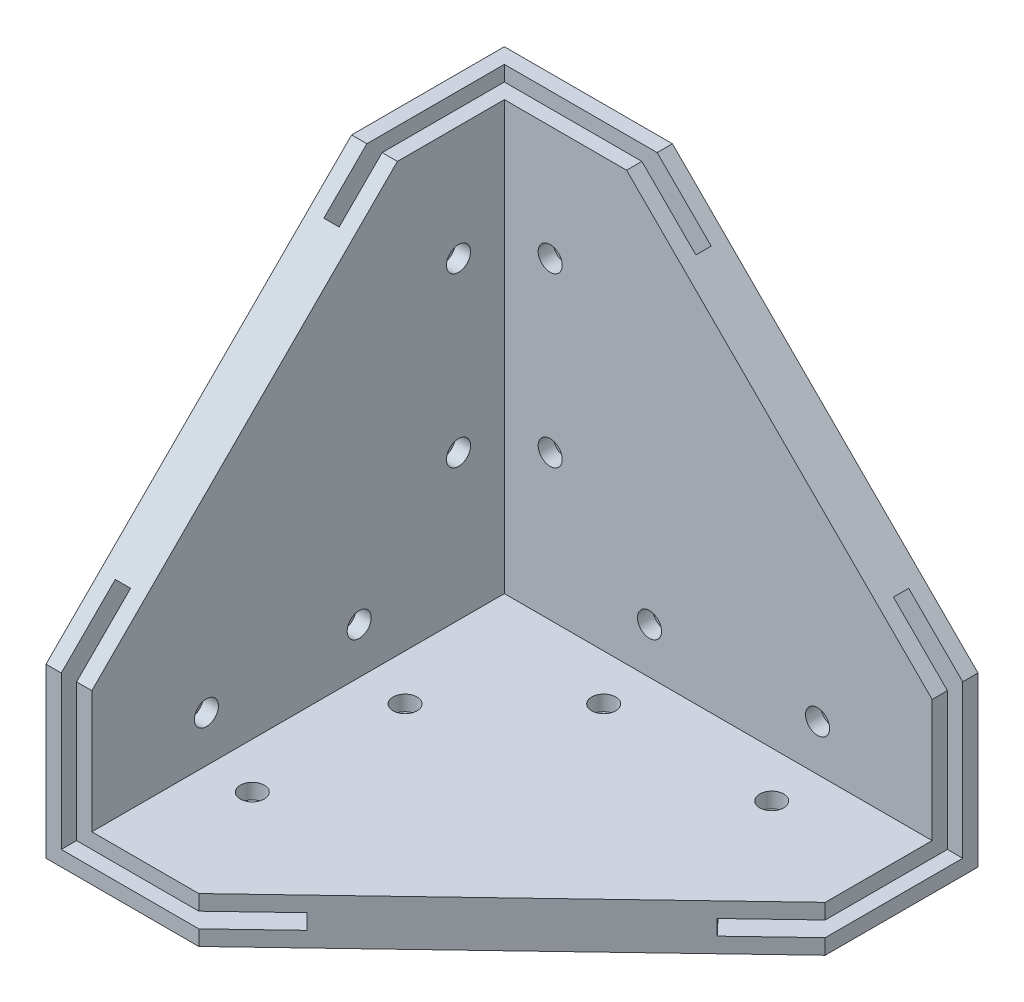
SolidWorks part; units mm, degrees
ref_plane "Front Plane" through (0, 0, 0) normal (0, 0, 1) x (1, 0, 0)
ref_plane "Top Plane" through (0, 0, 0) normal (0, 1, 0) x (1, 0, 0)
ref_plane "Right Plane" through (0, 0, 0) normal (1, 0, 0) x (0, 0, -1)
sketch "Sketch1" plane through (0, 0, 0) normal (0, 0, 1) x (1, 0, 0)
  line L0 (0, 76.2) -> (0, 0)
  line L1 (0, 0) -> (76.2, 0)
  line L2 (76.2, 0) -> (76.2, 25.4)
  line L3 (76.2, 25.4) -> (25.4, 76.2)
  line L4 (25.4, 76.2) -> (0, 76.2)
  dimension "D1" = 76.2
  dimension "D2" = 76.2
  dimension "D3" = 25.4
  dimension "D4" = 25.4
extrude "Boss-Extrude1" add sketch "Sketch1" along normal blind 2.54
sketch "Sketch3" plane through (0, 0, 0) normal (-1, 0, 0) x (0, 0, 1)
  line L0 (0, 76.2) -> (25.4, 76.2)
  line L2 (0, 76.2) -> (0, 0)
  line L3 (0, 0) -> (76.2, 0)
  line L4 (76.2, 0) -> (76.2, 25.4)
  line L6 (25.4, 76.2) -> (76.2, 25.4)
  dimension "D1" = 25.4
  dimension "D2" = 25.4
  dimension "D3" = 76.2
extrude "Boss-Extrude2" add sketch "Sketch3" along normal blind 2.54
sketch "Sketch5" plane through (0, 0, 0) normal (0, -1, 0) x (1, 0, 0)
  line L0 (-2.54, 76.2) -> (-2.54, 0)
  line L1 (-2.54, 0) -> (-2.54, 76.2) construction
  line L2 (-2.54, 0) -> (76.2, 0)
  line L3 (76.2, 0) -> (76.2, 25.4)
  line L4 (76.2, 25.4) -> (22.86, 76.2)
  line L5 (22.86, 76.2) -> (-2.54, 76.2)
  line L6 (-2.54, 76.2) -> (0, 76.2) construction
  dimension "D1" = 25.4
  dimension "D2" = 25.4
extrude "Boss-Extrude3" add sketch "Sketch5" along normal blind 2.54
sketch "Sketch6" plane through (0, 0, 0) normal (0, 0, 1) x (1, 0, 0)
  line L0 (22.86, 0) -> (0, 0) construction
  line L1 (2.54, 0) -> (5.08, 0)
  line L2 (2.54, 0) -> (2.54, 76.2)
  line L3 (2.54, 76.2) -> (5.08, 76.2)
  line L4 (5.08, 0) -> (5.08, 76.2)
  line L5 (25.4, 76.2) -> (0, 76.2) construction
  line L6 (0, 76.2) -> (0, 0) construction
  dimension "D1" = 2.54
  dimension "D2" = 2.54
extrude "Boss-Extrude4" add sketch "Sketch6" along direction (0, 0, -1) on the side of the normal blind 76.2
sketch "Sketch7" plane through (0, 0, 0) normal (1, 0, 0) x (0, 0, -1)
  line L0 (-25.4, 76.2) -> (-76.2, 25.4)
  line L1 (-76.2, 25.4) -> (-76.2, 76.2)
  line L2 (-76.2, 76.2) -> (-25.4, 76.2)
extrude "Cut-Extrude1" cut sketch "Sketch7" along normal up to next
sketch "Sketch8" plane through (0, 0, 0) normal (1, 0, 0) x (0, 0, -1)
  line L0 (-25.4, 76.2) -> (-2.54, 76.2) construction
  line L1 (-7.62, 76.2) -> (-5.08, 76.2)
  line L2 (-7.62, 76.2) -> (-7.62, -2.54)
  line L3 (-7.62, -2.54) -> (-5.08, -2.54)
  line L4 (-5.08, 76.2) -> (-5.08, -2.54)
  line L5 (0, -2.54) -> (-25.4, -2.54) construction
  line L6 (-2.54, 76.2) -> (-2.54, 0) construction
  dimension "D1" = 2.54
  dimension "D2" = 2.54
extrude "Boss-Extrude5" add sketch "Sketch8" along normal blind 76.2
sketch "Sketch9" plane through (0, 0, 0) normal (0, 0, 1) x (1, 0, 0)
  line L0 (76.2, 25.4) -> (25.4, 76.2)
  line L1 (25.4, 76.2) -> (76.2, 76.2)
  line L2 (76.2, 76.2) -> (76.2, 25.4)
extrude "Cut-Extrude2" cut sketch "Sketch9" along normal up to next
sketch "Sketch10" plane through (0, 0, 0) normal (0, 0, 1) x (1, 0, 0)
  line L0 (-2.54, -2.54) -> (-2.54, 25.4) construction
  line L1 (-2.54, 2.54) -> (76.2, 2.54)
  line L2 (-2.54, 2.54) -> (-2.54, 5.08)
  line L3 (-2.54, 5.08) -> (76.2, 5.08)
  line L4 (76.2, 2.54) -> (76.2, 5.08)
  line L5 (76.2, 25.4) -> (76.2, 0) construction
  line L6 (5.08, 0) -> (76.2, 0) construction
  dimension "D1" = 2.54
  dimension "D2" = 2.54
extrude "Boss-Extrude6" add sketch "Sketch10" along normal blind 76.2
sketch "Sketch11" plane through (0, 0, 0) normal (0, 1, 0) x (1, 0, 0)
  line L0 (22.86, -76.2) -> (76.2, -25.4)
  line L1 (76.2, -25.4) -> (76.2, -76.2)
  line L2 (76.2, -76.2) -> (22.86, -76.2)
extrude "Cut-Extrude3" cut sketch "Sketch11" along normal up to next
sketch "Sketch12" plane through (0, 0, 0) normal (1, 0, 0) x (0, 0, -1)
  line L0 (-5.08, 5.08) -> (-5.08, 2.54)
  line L1 (-5.08, 2.54) -> (-7.62, 2.54)
  line L2 (-7.62, 2.54) -> (-7.62, 0)
  line L3 (-7.62, 2.54) -> (-7.62, 0) construction
  line L4 (-7.62, 0) -> (-2.54, 0)
  line L5 (-2.54, 0) -> (-2.54, 5.08)
  line L6 (-2.54, 5.08) -> (-5.08, 5.08)
extrude "Cut-Extrude5" cut sketch "Sketch12" along normal through all
sketch "Sketch13" plane through (0, 0, 0) normal (0, 1, 0) x (1, 0, 0)
  line L0 (0, -2.54) -> (0, -7.62)
  line L1 (0, -7.62) -> (2.54, -7.62)
  line L2 (2.54, -7.62) -> (2.54, -5.08)
  line L3 (2.54, -5.08) -> (2.54, -2.54) construction
  line L4 (2.54, -5.08) -> (5.08, -5.08)
  line L5 (5.08, -5.08) -> (5.08, -2.54)
  line L6 (5.08, -2.54) -> (0, -2.54)
extrude "Cut-Extrude6" cut sketch "Sketch13" along normal through all
sketch "Sketch15" plane through (0, 0, 2.54) normal (0, 0, 1) x (1, 0, 0)
  line L0 (2.54, 5.08) -> (0, 5.08)
  line L1 (0, 5.08) -> (0, 0)
  line L2 (0, 0) -> (5.08, 0)
  line L3 (0, 0) -> (76.2, 0) construction
  line L4 (22.86, 0) -> (5.08, 0) construction
  line L5 (5.08, 0) -> (5.08, 2.54)
  line L6 (5.08, 0) -> (5.08, 2.54) construction
  line L7 (5.08, 2.54) -> (2.54, 2.54)
  line L8 (2.54, 2.54) -> (2.54, 5.08)
extrude "Cut-Extrude9" cut sketch "Sketch15" along normal blind 76.2
sketch "Sketch17" plane through (0, 0, 0) normal (0, 0, -1) x (-1, 0, 0)
  line L0 (-67.2197, 34.3803) -> (-34.3803, 67.2197)
  line L1 (-76.2, 25.4) -> (-25.4, 76.2) construction
  line L2 (-34.3803, 67.2197) -> (-30.7882, 63.6276)
  line L3 (-30.7882, 63.6276) -> (-63.6276, 30.7882)
  line L4 (-63.6276, 30.7882) -> (-67.2197, 34.3803)
  dimension "D1" = 12.7
  dimension "D2" = 12.7
  dimension "D3" = 5.08
extrude "Boss-Extrude7" add sketch "Sketch17" against normal up to surface (7.62 mm away) up to face at (37.592, 37.592, 7.62)
sketch "Sketch18" plane through (0, 0, 0) normal (0, 1, 0) x (1, 0, 0)
  line L0 (32.0566, -67.4414) -> (67.0034, -34.1586)
  line L1 (76.2, -25.4) -> (22.86, -76.2) construction
  line L2 (67.0034, -34.1586) -> (63.5, -30.48)
  line L3 (63.5, -30.48) -> (28.5531, -63.7628)
  line L4 (28.5531, -63.7628) -> (32.0566, -67.4414)
  dimension "D1" = 12.7
  dimension "D2" = 12.7
  dimension "D3" = 5.08
extrude "Boss-Extrude8" add sketch "Sketch18" along normal up to surface (5.08 mm away) up to face at (37.084, 5.08, 38.608)
sketch "Sketch19" plane through (0, 0, 0) normal (1, 0, 0) x (0, 0, -1)
  line L0 (-32.545, 69.055) -> (-67.2197, 34.3803)
  line L1 (-76.2, 25.4) -> (-25.4, 76.2) construction
  line L2 (-67.2197, 34.3803) -> (-63.6276, 30.7882)
  line L3 (-63.6276, 30.7882) -> (-28.9529, 65.4629)
  line L4 (-28.9529, 65.4629) -> (-32.545, 69.055)
  point P4 (-49.8824, 51.7176)
  dimension "D1" = 10.1046
  dimension "D2" = 12.7
  dimension "D3" = 5.08
extrude "Boss-Extrude9" add sketch "Sketch19" along normal up to surface (5.08 mm away) up to face at (5.08, 37.592, 38.608)
sketch "Sketch34" plane through (0, 0, 0) normal (1, 0, 0) x (0, 0, -1)
  line L0 (-15.24, 89.2211) -> (-15.24, -21.4288) construction
  line L1 (12.0246, 12.7) -> (-100.539, 12.7) construction
  line L2 (0, 76.2) -> (0, -2.54) construction
  line L3 (-76.2, -2.54) -> (0, -2.54) construction
  line L4 (19.1577, 57.15) -> (-54.087, 57.15) construction
  line L5 (19.1577, 29.21) -> (-54.087, 29.21) construction
  line L6 (-57.15, 27.3793) -> (-57.15, -35.5499) construction
  line L7 (-31.75, 27.3793) -> (-31.75, -35.5499) construction
  line L8 (-76.2, -2.54) -> (-76.2, 25.4) construction
  circle A0 centre (-15.24, 57.15) radius 2
  circle A1 centre (-15.24, 29.21) radius 2
  circle A2 centre (-31.75, 12.7) radius 2
  circle A3 centre (-57.15, 12.7) radius 2
  point P27 (0, 0)
  point P28 (-57.15, 12.7)
  dimension "D7" = 4
  dimension "D8" = 4
  dimension "D9" = 4
  dimension "D10" = 4
  dimension "D1" = 15.24
  dimension "D2" = 15.24
  dimension "D3" = 19.05
  dimension "D4" = 31.75
  dimension "D5" = 31.75
  dimension "D6" = 19.05
extrude "Cut-Extrude11" cut sketch "Sketch34" against normal mid plane 25.4
sketch "Sketch35" plane through (0, 0, 0) normal (0, 1, 0) x (1, 0, 0)
  line L0 (12.7, -87.9891) -> (12.7, 14.1496) construction
  line L1 (-2.54, -76.2) -> (-2.54, 0) construction
  line L2 (-9.517, -15.24) -> (98.4386, -15.24) construction
  line L3 (-2.54, 0) -> (76.2, 0) construction
  line L4 (-9.517, -57.15) -> (98.4386, -57.15) construction
  line L5 (22.86, -76.2) -> (-2.54, -76.2) construction
  line L6 (-9.517, -31.75) -> (98.4386, -31.75) construction
  line L7 (57.15, 14.1496) -> (57.15, -87.9891) construction
  line L8 (57.15, -87.9891) -> (57.15, 14.1496) construction
  line L9 (29.21, -87.9891) -> (29.21, 14.1496) construction
  line L10 (76.2, 0) -> (76.2, -25.4) construction
  circle A0 centre (12.7, -57.15) radius 2
  circle A1 centre (12.7, -31.75) radius 2
  circle A2 centre (29.21, -15.24) radius 2
  circle A3 centre (57.15, -15.24) radius 2
  dimension "D7" = 4
  dimension "D8" = 4
  dimension "D9" = 4
  dimension "D10" = 4
  dimension "D1" = 15.24
  dimension "D2" = 15.24
  dimension "D3" = 19.05
  dimension "D4" = 31.75
  dimension "D5" = 31.75
  dimension "D6" = 19.05
extrude "Cut-Extrude13" cut sketch "Sketch35" against normal mid plane 25.4
sketch "Sketch36" plane through (0, 0, 0) normal (0, 0, 1) x (1, 0, 0)
  line L0 (110.2526, 12.7) -> (-20.6631, 12.7) construction
  line L1 (12.7, 92.1582) -> (12.7, -15.0496) construction
  line L2 (-2.54, 76.2) -> (-2.54, -2.54) construction
  line L3 (-2.54, -2.54) -> (76.2, -2.54) construction
  line L4 (57.15, 92.1582) -> (57.15, -15.0496) construction
  line L5 (29.21, 92.1582) -> (29.21, -15.0496) construction
  line L6 (-20.6631, 29.21) -> (46.0631, 29.21) construction
  line L7 (-20.6631, 57.15) -> (110.2526, 57.15) construction
  line L8 (25.4, 76.2) -> (-2.54, 76.2) construction
  line L9 (76.2, -2.54) -> (76.2, 25.4) construction
  circle A0 centre (57.15, 12.7) radius 2
  circle A1 centre (29.21, 12.7) radius 2
  circle A2 centre (12.7, 29.21) radius 2
  circle A3 centre (12.7, 57.15) radius 2
  point P28 (12.7, 29.21)
  point P29 (12.7, 40.7367)
  dimension "D7" = 4
  dimension "D8" = 4
  dimension "D9" = 4
  dimension "D10" = 4
  dimension "D1" = 15.24
  dimension "D2" = 15.24
  dimension "D3" = 19.05
  dimension "D4" = 31.75
  dimension "D5" = 19.05
  dimension "D6" = 31.75
extrude "Cut-Extrude14" cut sketch "Sketch36" against normal mid plane 25.4
